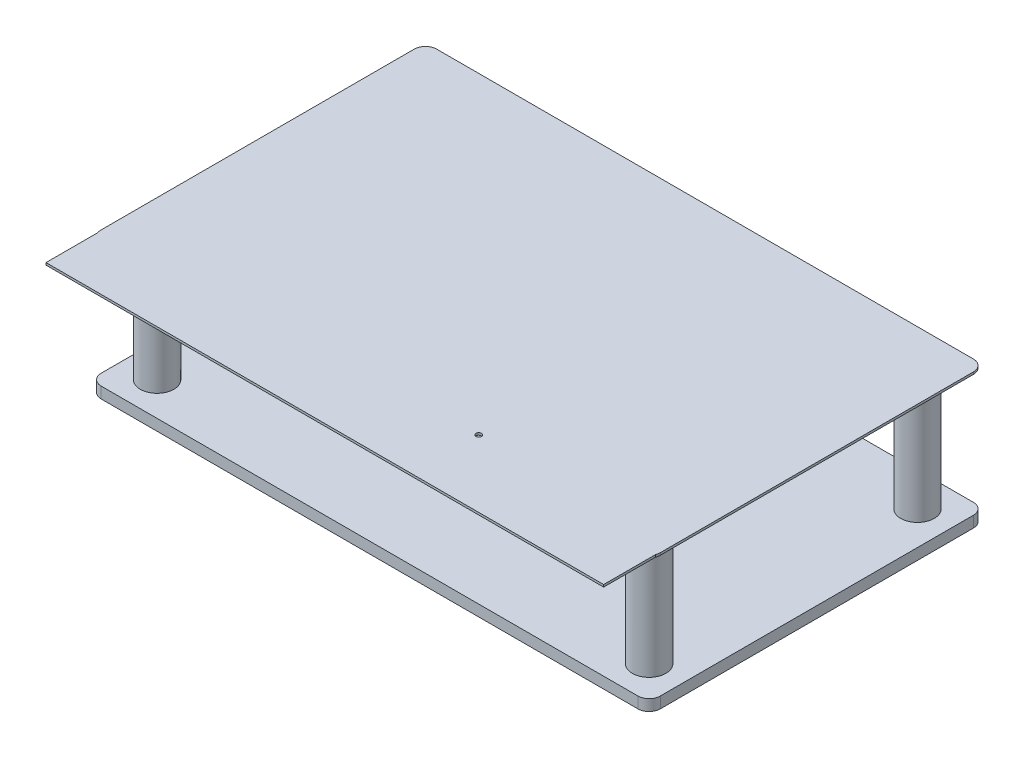
SolidWorks part; units mm, degrees
ref_plane "Front Plane" through (0, 0, 0) normal (0, 0, 1) x (1, 0, 0)
ref_plane "Top Plane" through (0, 0, 0) normal (0, 1, 0) x (1, 0, 0)
ref_plane "Right Plane" through (0, 0, 0) normal (1, 0, 0) x (0, 0, -1)
sketch "Sketch1" plane through (0, 0, 0) normal (0, 1, 0) x (1, 0, 0)
  line L1 (-240, 150) -> (240, 150)
  line L2 (-250, 140) -> (-250, -140)
  line L3 (-240, -150) -> (240, -150)
  line L4 (250, 140) -> (250, -140)
  line L5 (-250, 150) -> (250, -150) construction
  line L6 (-250, -150) -> (250, 150) construction
  arc A0 (240, 150) -> (250, 140) centre (240, 140) cw
  arc A1 (240, -150) -> (250, -140) centre (240, -140) ccw
  arc A2 (-250, -140) -> (-240, -150) centre (-240, -140) ccw
  arc A3 (-240, 150) -> (-250, 140) centre (-240, 140) ccw
  point P0 (0, 0)
  dimension "D3" = 10
  dimension "D1" = 500
  dimension "D2" = 300
extrude "Boss-Extrude1" add sketch "Sketch1" along normal blind 10
sketch "Sketch2" plane through (0, 10, 0) normal (0, 1, 0) x (1, 0, 0)
  line L0 (-250, 140) -> (-250, -140) construction
  line L1 (240, 150) -> (-240, 150) construction
  line L2 (0, -5.5) -> (0, 5.5) construction
  line L3 (-5.5, 0) -> (5.5, 0) construction
  circle A0 centre (-220, 120) radius 15
  circle A1 centre (220, 120) radius 15
  circle A2 centre (220, -120) radius 15
  circle A3 centre (-220, -120) radius 15
  dimension "D1" = 30
  dimension "D2" = 30
  dimension "D3" = 30
extrude "Boss-Extrude2" add sketch "Sketch2" along normal blind 109
sketch "Sketch3" plane through (0, 119, 0) normal (0, 1, 0) x (1, 0, 0)
  line L1 (-240, 150) -> (240, 150)
  line L2 (-250, 140) -> (-250, -140)
  line L3 (-240, -150) -> (240, -150)
  line L4 (250, 140) -> (250, -140)
  line L5 (-250, 150) -> (250, -150) construction
  line L6 (-250, -150) -> (250, 150) construction
  arc A0 (240, -150) -> (250, -140) centre (240, -140) ccw
  arc A1 (240, 150) -> (250, 140) centre (240, 140) cw
  arc A2 (-250, -140) -> (-240, -150) centre (-240, -140) ccw
  arc A3 (-240, 150) -> (-250, 140) centre (-240, 140) ccw
  point P0 (0, 0)
  dimension "D1" = 10
extrude "Boss-Extrude3" add sketch "Sketch3" along normal blind 2
sketch "Sketch4" plane through (0, 121, 0) normal (0, 1, 0) x (1, 0, 0)
  line L0 (-240, -150) -> (240, -150) construction
  line L1 (-249.3504, -110) -> (249.3504, -110)
  line L2 (-249.3504, -110) -> (-249.3504, -190)
  line L3 (-249.3504, -190) -> (249.3504, -190)
  line L4 (249.3504, -110) -> (249.3504, -190)
  line L5 (-249.3504, -110) -> (249.3504, -190) construction
  line L6 (-249.3504, -190) -> (249.3504, -110) construction
  point P0 (0, -150)
  dimension "D1" = 80
extrude "Boss-Extrude4" add sketch "Sketch4" against normal blind 2
sketch "Sketch5" plane through (0, 121, 0) normal (0, 1, 0) x (1, 0, 0)
  line L0 (-249.3504, -190) -> (249.3504, -190) construction
  line L1 (249.3504, -190) -> (249.3504, -143.5455) construction
  circle A0 centre (77.6304, -130) radius 2.5
  dimension "D1" = 5
  dimension "D2" = 60
  dimension "D3" = 171.72
extrude "Cut-Extrude1" cut sketch "Sketch5" against normal blind 20
